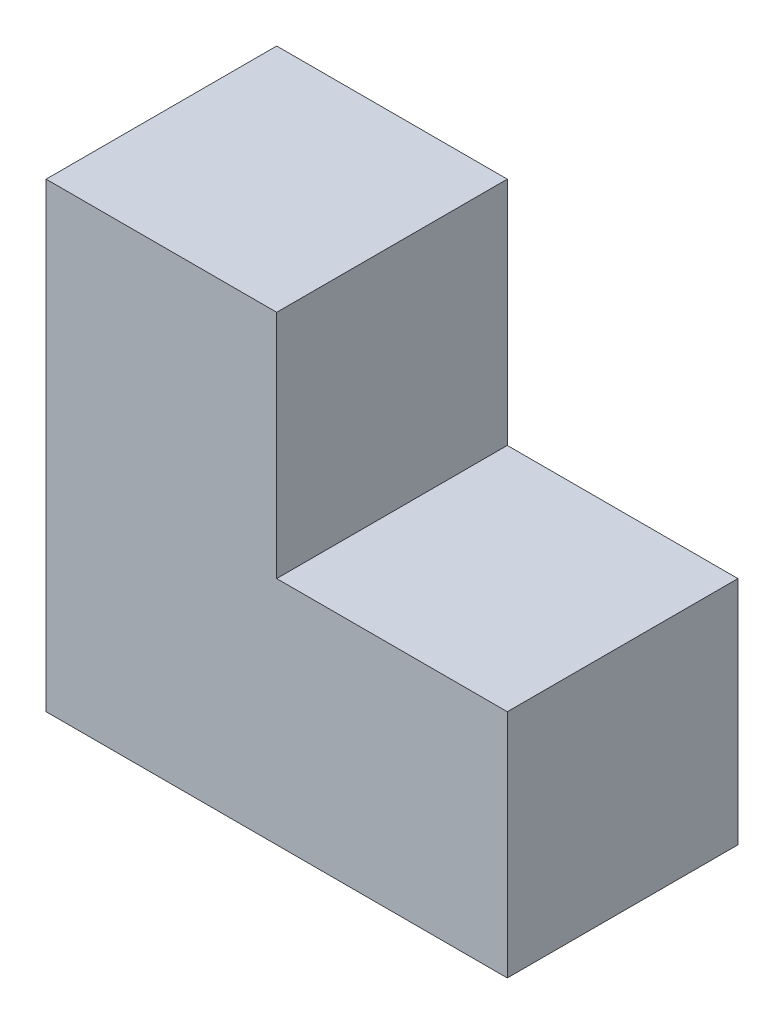
SolidWorks part; units mm, degrees
ref_plane "Plan de face" through (0, 0, 0) normal (0, 0, 1) x (1, 0, 0)
ref_plane "Plan de dessus" through (0, 0, 0) normal (0, 1, 0) x (1, 0, 0)
ref_plane "Plan de droite" through (0, 0, 0) normal (1, 0, 0) x (0, 0, -1)
sketch "Esquisse1" plane through (0, 0, 0) normal (0, 0, 1) x (1, 0, 0)
  line L0 (0, 0) -> (0, 600)
  line L1 (0, 600) -> (300, 600)
  line L2 (300, 600) -> (300, 300)
  line L3 (300, 300) -> (600, 300)
  line L4 (600, 300) -> (600, 0)
  line L5 (600, 0) -> (0, 0)
  dimension "D1" = 600
  dimension "D2" = 300
  dimension "D3" = 600
  dimension "D4" = 300
extrude "Boss.-Extru.1" add sketch "Esquisse1" along normal blind 300
